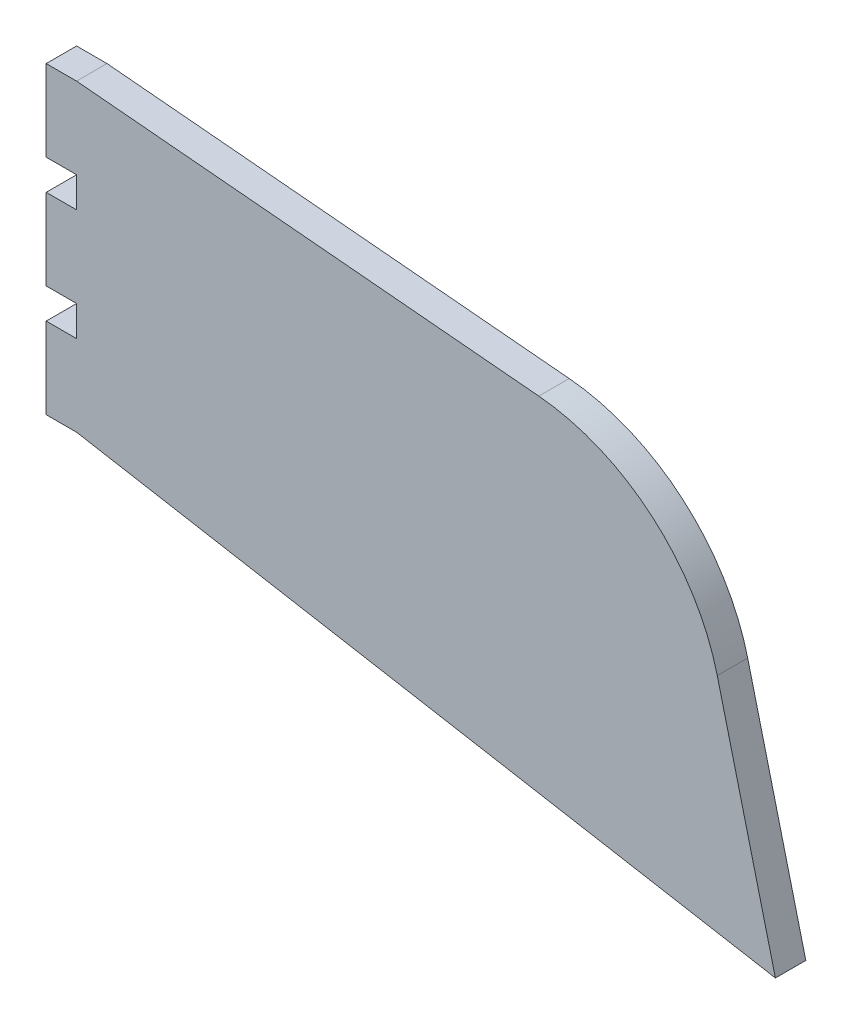
SolidWorks part; units mm, degrees
ref_plane "Plan de face" through (0, 0, 0) normal (0, 0, 1) x (1, 0, 0)
ref_plane "Plan de dessus" through (0, 0, 0) normal (0, 1, 0) x (1, 0, 0)
ref_plane "Plan de droite" through (0, 0, 0) normal (1, 0, 0) x (0, 0, -1)
sketch "Esquisse1" plane through (0, 0, 0) normal (0, 0, 1) x (1, 0, 0)
  line L0 (-68.9365, 12.1554) -> (0, 0)
  line L1 (-68.9365, 42.1554) -> (-9.179, 36.7664)
  line L2 (-9.179, 36.7664) -> (0, 0)
  line L3 (-68.9365, 42.1554) -> (-68.9365, 12.1554)
  line L4 (-71.9365, 34.1554) -> (-71.9365, 31.1554)
  line L5 (-68.9365, 42.1554) -> (-71.9365, 42.1554)
  line L6 (-68.9365, 42.1554) -> (-68.9365, 34.1554)
  line L7 (-68.9365, 34.1554) -> (-71.9365, 34.1554)
  line L8 (-71.9365, 42.1554) -> (-71.9365, 34.1554)
  line L9 (-68.9365, 12.1554) -> (-71.9365, 12.1554)
  line L10 (-68.9365, 12.1554) -> (-68.9365, 20.1554)
  line L11 (-68.9365, 20.1554) -> (-71.9365, 20.1554)
  line L12 (-71.9365, 12.1554) -> (-71.9365, 20.1554)
  line L13 (-68.9365, 31.1554) -> (-71.9365, 31.1554)
  line L14 (-68.9365, 31.1554) -> (-68.9365, 23.1554)
  line L15 (-68.9365, 23.1554) -> (-71.9365, 23.1554)
  line L16 (-71.9365, 31.1554) -> (-71.9365, 23.1554)
  line L17 (-71.9365, 23.1554) -> (-71.9365, 20.1554)
  point P0 (-68.9365, 12.1554)
  point P1 (-68.9365, 42.1554)
  dimension "D1" = 30
  dimension "D2" = 70
  dimension "D3" = 60
  dimension "D4" = 100
  dimension "D5" = 36.7664
  dimension "D6" = 3
  dimension "D7" = 8
extrude "Boss.-Extru.1" add sketch "Esquisse1" along normal blind 3 contours L1 L3 L0 L2 | L5 L8 L7 L3 | L13 L16 L15 L3 | L12 L9 L3 L11
fillet "Congé1" radius 20 1 edges at (-9.179, 36.7664, 1.5)
